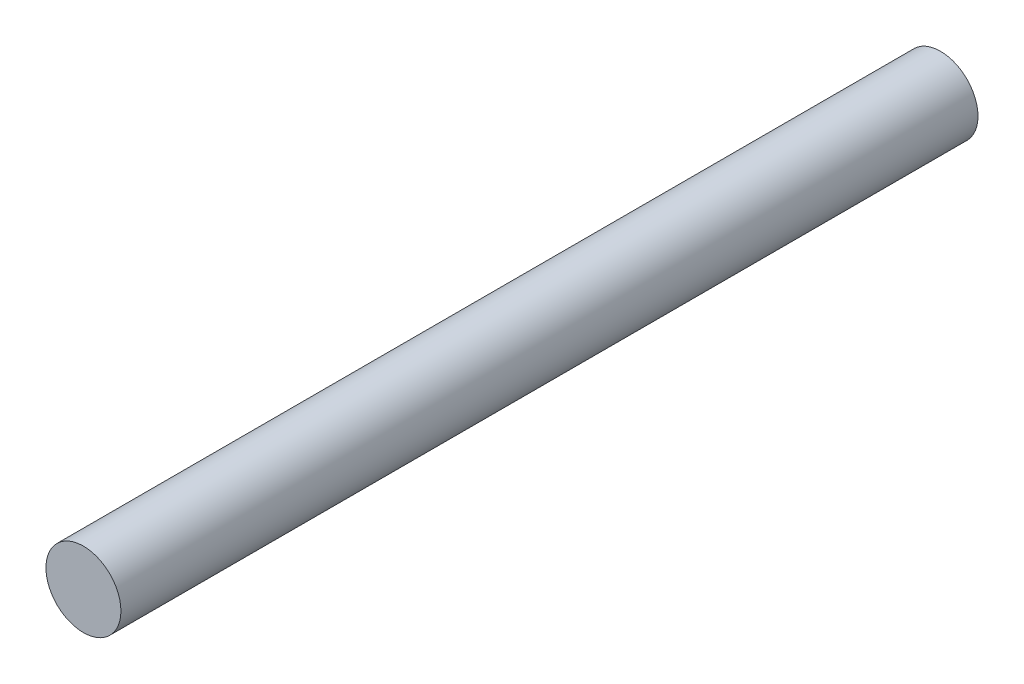
SolidWorks part; units mm, degrees
material "AISI 1020"
ref_plane "Front Plane" through (0, 0, 0) normal (0, 0, 1) x (1, 0, 0)
ref_plane "Top Plane" through (0, 0, 0) normal (0, 1, 0) x (1, 0, 0)
ref_plane "Right Plane" through (0, 0, 0) normal (1, 0, 0) x (0, 0, -1)
sketch "Sketch2" plane through (0, 0, 0) normal (0, 0, 1) x (1, 0, 0)
  circle A0 centre (0, 0) radius 4.5
ref_plane "Plane1" through (0, 0, 25.4) normal (0, 0, 1) x (1, 0, 0)
sketch "Sketch3" plane through (0, 0, 25.4) normal (0, 0, 1) x (1, 0, 0)
  line L0 (-3.9226, 2.2053) -> (3.9226, 2.2053)
  circle A0 centre (0, 0) radius 4.5
ref_plane "Plane2" through (0, 0, 88.9) normal (0, 0, 1) x (1, 0, 0)
sketch "Sketch4" plane through (0, 0, 88.9) normal (0, 0, 1) x (1, 0, 0)
  circle A0 centre (0, 0) radius 5
  dimension "D1" = 10
extrude "Boss-Extrude1" add sketch "Sketch4" along normal blind 114.3
